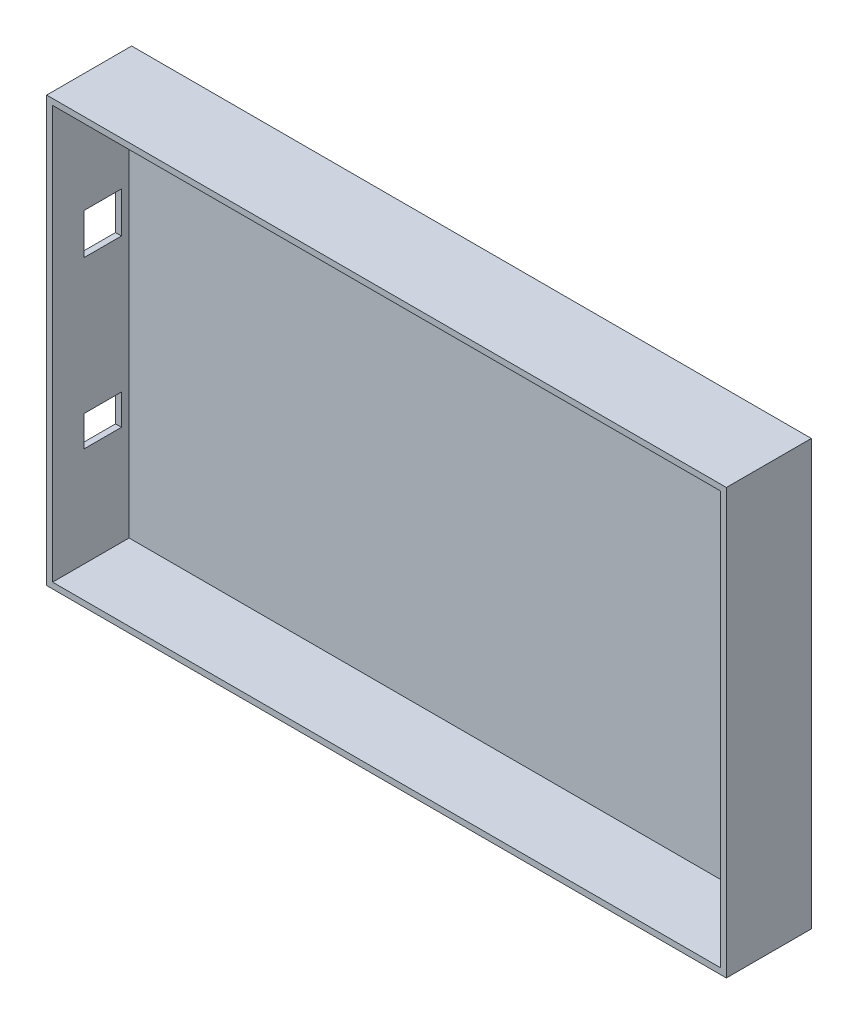
SolidWorks part; units mm, degrees
ref_plane "Front" through (0, 0, 0) normal (0, 0, 1) x (1, 0, 0)
ref_plane "Top" through (0, 0, 0) normal (0, 1, 0) x (1, 0, 0)
ref_plane "Right" through (0, 0, 0) normal (1, 0, 0) x (0, 0, -1)
sketch "Sketch1" plane through (0, 0, 0) normal (0, 0, 1) x (1, 0, 0)
  line L1 (0, 0) -> (203.2, 0)
  line L2 (0, 0) -> (0, 127)
  line L3 (0, 127) -> (203.2, 127)
  line L4 (203.2, 0) -> (203.2, 127)
  dimension "D1" = 203.2
  dimension "D2" = 127
extrude "Boss-Extrude1" add sketch "Sketch1" along normal blind 25.4
sketch "Sketch2" plane through (0, 0, 25.4) normal (0, 0, 1) x (1, 0, 0)
  line L0 (101.6, 127) -> (101.6, 0) construction
  line L1 (203.2, 127) -> (0, 127) construction
  line L2 (0, 0) -> (203.2, 0) construction
  line L3 (0, 127) -> (0, 0) construction
  line L4 (1.778, 125.222) -> (201.422, 125.222)
  line L5 (1.778, 125.222) -> (1.778, 1.778)
  line L6 (1.778, 1.778) -> (201.422, 1.778)
  line L7 (201.422, 125.222) -> (201.422, 1.778)
  line L8 (203.2, 0) -> (203.2, 127) construction
  point P13 (1.778, 63.5)
  dimension "D1" = 1.778
  dimension "D2" = 1.778
  dimension "D3" = 1.778
  dimension "D4" = 1.778
extrude "Cut-Extrude1" cut sketch "Sketch2" against normal blind 22.86
sketch "Sketch4" plane through (0, 0, 0) normal (-1, 0, 0) x (0, 0, 1)
  line L0 (0, 127) -> (0, 0) construction
  line L1 (16.002, 93.3029) -> (4.826, 93.3029)
  line L2 (16.002, 93.3029) -> (16.002, 81.1109)
  line L3 (16.002, 81.1109) -> (4.826, 81.1109)
  line L4 (4.826, 93.3029) -> (4.826, 81.1109)
  line L5 (16.002, 40.7249) -> (4.826, 40.7249)
  line L6 (16.002, 40.7249) -> (16.002, 31.5809)
  line L7 (16.002, 31.5809) -> (4.826, 31.5809)
  line L8 (4.826, 40.7249) -> (4.826, 31.5809)
  point P10 (16.002, 36.1529)
  dimension "D1" = 12.192
  dimension "D2" = 11.176
  dimension "D3" = 16.002
  dimension "D4" = 9.144
  dimension "D5" = 11.176
  dimension "D6" = 16.002
  dimension "D7" = 40.386
extrude "Cut-Extrude2" cut sketch "Sketch4" against normal blind 1.778
